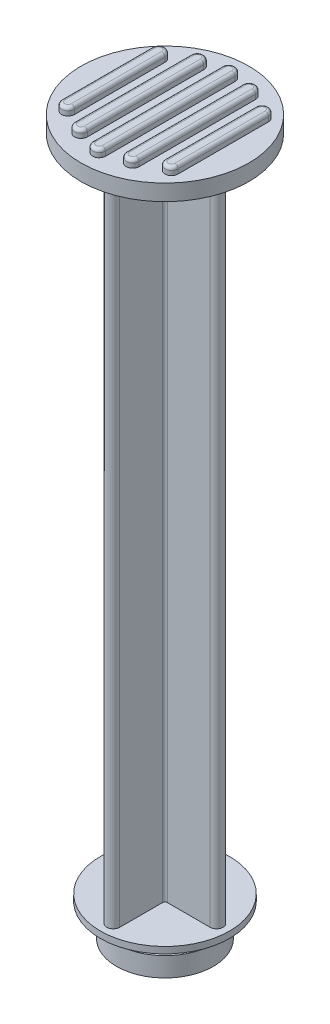
SolidWorks part; units mm, degrees
ref_plane "Front Plane" through (0, 0, 0) normal (0, 0, 1) x (1, 0, 0)
ref_plane "Top Plane" through (0, 0, 0) normal (0, 1, 0) x (1, 0, 0)
ref_plane "Right Plane" through (0, 0, 0) normal (1, 0, 0) x (0, 0, -1)
sketch "Sketch1" plane through (0, 0, 0) normal (0, 0, 1) x (1, 0, 0)
  line L0 (0, 0) -> (7.5, 0)
  line L1 (7.5, 3) -> (7.5, 0)
  line L2 (7.5, 3) -> (6, 3)
  line L3 (6, 3) -> (6, 5)
  line L4 (6, 5) -> (10, 5)
  line L5 (10, 5) -> (10, 6)
  line L6 (10, 6) -> (0, 6)
  line L7 (0, 6) -> (0, 0)
  dimension "D1" = 3
  dimension "D2" = 2
  dimension "D3" = 1
  dimension "D4" = 6
  dimension "D5" = 7.5
  dimension "D6" = 10
revolve "Revolve1" add sketch "Sketch1" angle 360 about L7
sketch "Sketch2" plane through (0, 6, 0) normal (0, 1, 0) x (1, 0, 0)
  line L0 (0, 10) -> (0, -10) construction
  line L1 (10, 0) -> (-10, 0) construction
  line L2 (-1, 8) -> (-1, 1.3778)
  line L3 (8, 1) -> (1.3778, 1)
  line L4 (1, 8) -> (1, 1.3778)
  line L5 (8, -1) -> (1.3778, -1)
  line L6 (1, -1.3778) -> (1, -8)
  line L7 (1, 10) -> (1, -10) construction
  line L8 (-1, 10) -> (-1, -10) construction
  line L9 (10, 1) -> (-10, 1) construction
  line L10 (10, -1) -> (-10, -1) construction
  line L11 (-1.3778, 1) -> (-8, 1)
  line L12 (-1.3778, -1) -> (-8, -1)
  line L13 (-1, -1.3778) -> (-1, -8)
  circle A0 centre (0, 0) radius 10 construction
  arc A1 (1, 8) -> (-1, 8) centre (0, 8) ccw
  arc A2 (-8, 1) -> (-8, -1) centre (-8, 0) ccw
  arc A3 (8, -1) -> (8, 1) centre (8, 0) ccw
  arc A4 (-1, -8) -> (1, -8) centre (0, -8) ccw
  arc A5 (1, 1.3778) -> (1.3778, 1) centre (1.3778, 1.3778) ccw
  arc A6 (-1.3778, 1) -> (-1, 1.3778) centre (-1.3778, 1.3778) ccw
  arc A7 (-1.3778, -1) -> (-1, -1.3778) centre (-1.3778, -1.3778) cw
  arc A8 (1.3778, -1) -> (1, -1.3778) centre (1.3778, -1.3778) ccw
  point P38 (-1, -1)
  dimension "D7" = 0.3778
  dimension "D3" = 8
  dimension "D4" = 8
  dimension "D5" = 8
  dimension "D6" = 8
  dimension "D1" = 1
  dimension "D2" = 1
extrude "Boss-Extrude1" add sketch "Sketch2" along normal blind 102
sketch "Sketch3" plane through (0, 108, 0) normal (0, 1, 0) x (1, 0, 0)
  circle A0 centre (0, 0) radius 13
  dimension "D1" = 26
extrude "Boss-Extrude2" add sketch "Sketch3" along normal blind 2.5
sketch "Sketch4" plane through (0, 110.5, 0) normal (0, 1, 0) x (1, 0, 0)
  line L0 (-13, 0) -> (13, 0) construction
  line L2 (0, -13) -> (0, 13) construction
  line L3 (3.9997, -8.9846) -> (3.9997, 9.0154) construction
  line L10 (7.9997, -6.9795) -> (7.9997, 7.0205) construction
  line L14 (-4, -9) -> (-4, 9) construction
  line L21 (-8, -7) -> (-8, 7) construction
  line L22 (8.9997, -6.9795) -> (8.9997, 7.0205)
  line L28 (4.9997, -8.9846) -> (4.9997, 9.0154)
  line L29 (1, -10.2298) -> (1, 9.8599)
  line L30 (-3, -9) -> (-3, 9)
  line L31 (-7, -7) -> (-7, 7)
  line L32 (6.9997, -6.9795) -> (6.9997, 7.0205)
  line L33 (2.9997, -8.9846) -> (2.9997, 9.0154)
  line L34 (-1, -10.2298) -> (-1, 9.8599)
  line L35 (-5, -9) -> (-5, 9)
  line L36 (-9, -7) -> (-9, 7)
  line L38 (1, -13) -> (1, 13) construction
  line L39 (-1, -13) -> (-1, 13) construction
  circle A17 centre (0, 0) radius 13 construction
  arc A18 (6.9997, -6.9795) -> (8.9997, -6.9795) centre (7.9997, -6.9795) ccw
  arc A19 (2.9997, -8.9846) -> (4.9997, -8.9846) centre (3.9997, -8.9846) ccw
  arc A20 (-5, -9) -> (-3, -9) centre (-4, -9) ccw
  arc A21 (-9, -7) -> (-7, -7) centre (-8, -7) ccw
  arc A22 (-1, -10.1401) -> (1, -10.2298) centre (0, -10.185) ccw
  arc A23 (6.9997, 7.0205) -> (8.9997, 7.0205) centre (7.9997, 7.0205) cw
  arc A24 (2.9997, 9.0154) -> (4.9997, 9.0154) centre (3.9997, 9.0154) cw
  arc A25 (-1, 9.8599) -> (1, 9.8599) centre (0, 9.8599) cw
  arc A26 (-5, 9) -> (-3, 9) centre (-4, 9) cw
  arc A27 (-9, 7) -> (-7, 7) centre (-8, 7) cw
  point P5 (0, 0)
  point P6 (0, 9.8599)
  point P7 (0, 10)
  point P8 (0, -9.0505)
  point P9 (0, -10)
  point P10 (0, -10.1401)
  dimension "D1" = 1
  dimension "D2" = 1
extrude "Boss-Extrude4" add sketch "Sketch4" along normal blind 1.2 contours A23 L32 A18 L22 | A24 L33 A19 L28 | A25 L34 A22 L29 | A26 L35 A20 L30 | A27 L36 A21 L31
fillet "Fillet1" radius 0.5 20 edges at (-7, 111.7, 0) (-8, 111.7, 8) (-9, 111.7, 0) (-8, 111.7, -8) (-3, 111.7, 0) (-4, 111.7, 10) (-5, 111.7, 0) (-4, 111.7, -10) (1, 111.7, 0.185) (0, 111.7, 11.186) (-1, 111.7, 0.185) (0, 111.7, -10.8599) (4.9997, 111.7, -0.0154) (3.9997, 111.7, 9.9846) (2.9997, 111.7, -0.0154) (3.9997, 111.7, -10.0154) (8.9997, 111.7, -0.0205) (7.9997, 111.7, 7.9795) (6.9997, 111.7, -0.0205) (7.9997, 111.7, -8.0205)
